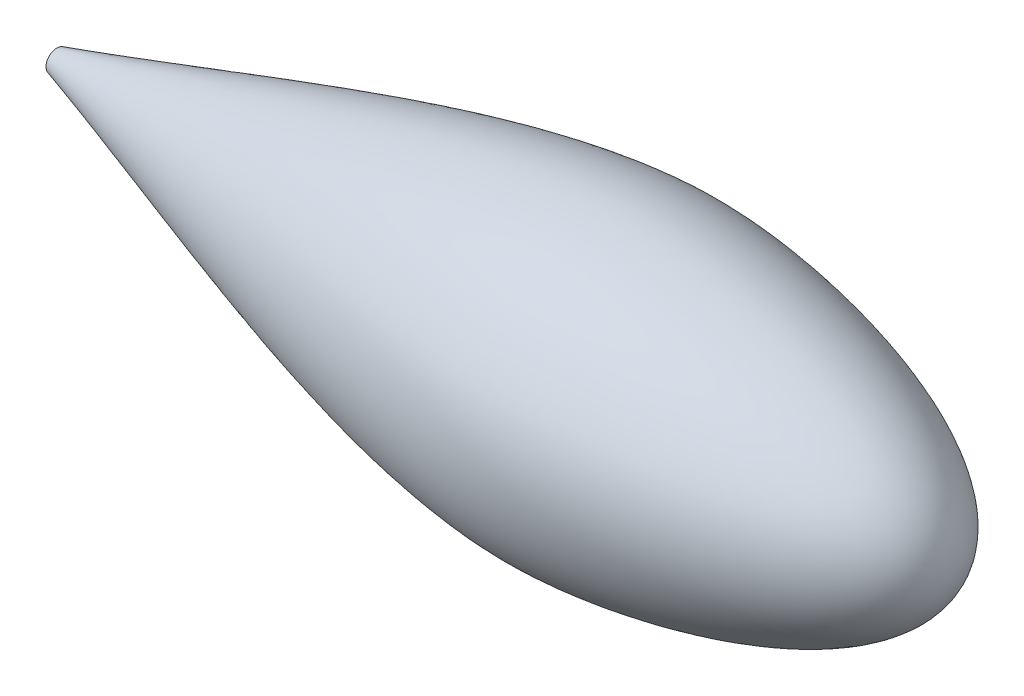
SolidWorks part; units mm, degrees
ref_plane "Plan de face" through (0, 0, 0) normal (0, 0, 1) x (1, 0, 0)
ref_plane "Plan de dessus" through (0, 0, 0) normal (0, 1, 0) x (1, 0, 0)
ref_plane "Plan de droite" through (0, 0, 0) normal (1, 0, 0) x (0, 0, -1)
sketch "Esquisse1" plane through (0, 0, 0) normal (0, 1, 0) x (1, 0, 0)
  line L0 (-250, 0) -> (0, 0)
  line L1 (0, 0) -> (55.3041, 0) construction
  spline S0 degree 3 poles (0, 0) (0, 24.7797) (-64.4648, 41.302) (-140.8942, 38.2932) (-203.3857, 13.1243) (-250, 0) knots 0 0 0 0 0.334424 0.434424 1 1 1 1
  dimension "D1" = 250
  dimension "D2" = 40
revolve "Révolution1" add sketch "Esquisse1" angle 360 about L1
ref_plane "Plan1" through (-240, 0, 0) normal (1, 0, 0) x (0, 0, -1)
sketch "Esquisse2" plane through (-240, 0, 0) normal (1, 0, 0) x (0, 0, -1)
  line L1 (-20.8355, -17.777) -> (20.8355, -17.777)
  line L2 (-20.8355, -17.777) -> (-20.8355, 17.777)
  line L3 (-20.8355, 17.777) -> (20.8355, 17.777)
  line L4 (20.8355, -17.777) -> (20.8355, 17.777)
  line L5 (-20.8355, -17.777) -> (20.8355, 17.777) construction
  line L6 (-20.8355, 17.777) -> (20.8355, -17.777) construction
  point P0 (0, 0)
extrude "Enlèv. mat.-Extru.1" cut sketch "Esquisse2" against normal blind 56
sketch "Esquisse3" plane through (0, 0, 0) normal (0, 1, 0) x (1, 0, 0)
  line L0 (0, 0) -> (10, 0) construction
  dimension "D1" = 10
